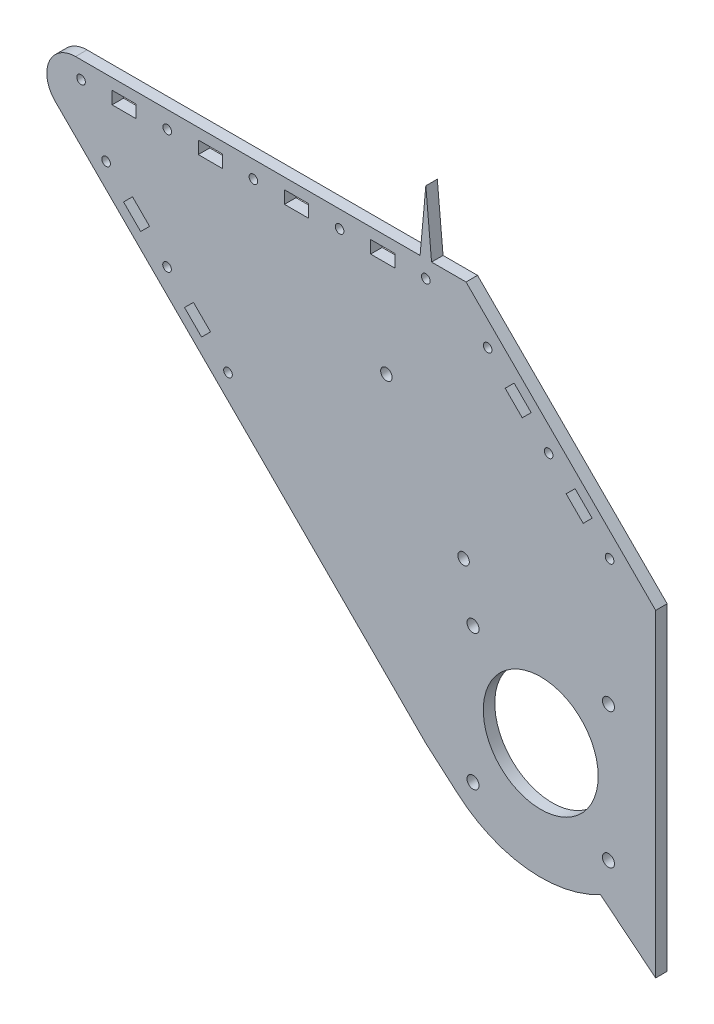
SolidWorks part; units mm, degrees
ref_plane "前视基准面" through (0, 0, 0) normal (0, 0, 1) x (1, 0, 0)
ref_plane "上视基准面" through (0, 0, 0) normal (0, 1, 0) x (1, 0, 0)
ref_plane "右视基准面" through (0, 0, 0) normal (1, 0, 0) x (0, 0, -1)
sketch "草图1" plane through (0, 0, 0) normal (0, 0, 1) x (1, 0, 0)
  line L261 (47.0274, 35.0547) -> (47.0274, 15.0547) construction
  line L315 (7.0274, -5.0025) -> (18.1903, -14.687)
  line L316 (-52.9726, 135.0547) -> (-52.9726, 126.7057) construction
  line L332 (-112.9726, 135.0547) -> (-97.9726, 135.0547) construction
  line L334 (-42.1726, 137.2547) -> (-33.7726, 137.2547)
  line L335 (-42.1726, 137.2547) -> (-42.1726, 132.8547)
  line L336 (-42.1726, 132.8547) -> (-33.7726, 132.8547)
  line L337 (-33.7726, 137.2547) -> (-33.7726, 132.8547)
  line L338 (-42.1726, 137.2547) -> (-33.7726, 132.8547) construction
  line L339 (-42.1726, 132.8547) -> (-33.7726, 137.2547) construction
  line L389 (-114.8877, 141.0547) -> (21.0274, 141.0547)
  line L390 (-22.9726, 135.0547) -> (-22.9726, 144.5851) construction
  line L395 (-37.9726, 135.0547) -> (-7.9726, 135.0547) construction
  line L418 (87.0274, 75.0547) -> (21.0274, 141.0547)
  line L419 (-3.7726, 132.8547) -> (-12.1726, 137.2547) construction
  line L420 (-3.7726, 137.2547) -> (-12.1726, 132.8547) construction
  line L421 (7.0274, 135.0547) -> (-7.9726, 135.0547) construction
  line L422 (-12.1726, 137.2547) -> (-12.1726, 132.8547)
  line L423 (-3.7726, 132.8547) -> (-12.1726, 132.8547)
  line L424 (-3.7726, 137.2547) -> (-3.7726, 132.8547)
  line L443 (-3.7726, 137.2547) -> (-12.1726, 137.2547)
  line L444 (-102.1726, 137.2547) -> (-93.7726, 132.8547) construction
  line L445 (-102.1726, 132.8547) -> (-93.7726, 137.2547) construction
  line L446 (7.0274, -5.0025) -> (-139.0298, 141.0547) construction
  line L447 (-67.9726, 135.0547) -> (-97.9726, 135.0547) construction
  line L448 (47.0274, 15.0547) -> (7.0431, -54.2363) construction
  line L449 (-63.7726, 132.8547) -> (-72.1726, 137.2547) construction
  line L483 (-63.7726, 137.2547) -> (-72.1726, 132.8547) construction
  line L515 (47.0274, 35.0547) -> (47.0274, 135.0547) construction
  line L516 (47.0274, 135.0547) -> (-52.9726, 135.0547) construction
  line L517 (-102.1726, 137.2547) -> (-93.7726, 137.2547)
  line L518 (-102.1726, 137.2547) -> (-102.1726, 132.8547)
  line L519 (-102.1726, 132.8547) -> (-93.7726, 132.8547)
  line L520 (-93.7726, 137.2547) -> (-93.7726, 132.8547)
  line L521 (-72.1726, 137.2547) -> (-72.1726, 132.8547)
  line L522 (-63.7726, 132.8547) -> (-72.1726, 132.8547)
  line L523 (-63.7726, 137.2547) -> (-63.7726, 132.8547)
  line L524 (-63.7726, 137.2547) -> (-72.1726, 137.2547)
  line L525 (7.0274, -5.0025) -> (-7.4159, -49.5482) construction
  line L551 (7.0274, -5.0025) -> (87.0274, -5.0025) construction
  line L552 (7.0274, -5.0025) -> (7.0274, 75.0547) construction
  line L553 (7.0274, 75.0547) -> (87.0274, 75.0547) construction
  line L554 (87.0274, -5.0025) -> (87.0274, 75.0547)
  line L555 (87.0274, -5.0025) -> (17.0006, -65.7205) construction
  line L556 (21.4033, 132.1936) -> (81.3921, 72.2048) construction
  line L557 (54.0274, 108.0547) -> (35.0674, 89.0947) construction
  line L558 (43.7037, 113.0045) -> (34.6527, 115.8329) construction
  line L559 (55.8659, 94.6197) -> (61.8056, 88.68)
  line L576 (55.8659, 94.6197) -> (58.9772, 97.731)
  line L577 (58.9772, 97.731) -> (64.9169, 91.7913)
  line L578 (61.8056, 88.68) -> (64.9169, 91.7913)
  line L579 (55.8659, 94.6197) -> (64.9169, 91.7913) construction
  line L580 (58.9772, 97.731) -> (61.8056, 88.68) construction
  line L581 (40.5924, 109.8932) -> (37.764, 118.9442) construction
  line L582 (34.6527, 115.8329) -> (37.764, 118.9442)
  line L583 (43.7037, 113.0045) -> (37.764, 118.9442)
  line L584 (40.5924, 109.8932) -> (43.7037, 113.0045)
  line L585 (40.5924, 109.8932) -> (34.6527, 115.8329)
  line L586 (60.3914, 93.2055) -> (58.8358, 91.6499) construction
  line L587 (39.1782, 114.4187) -> (37.6226, 112.8631) construction
  line L594 (75.8488, -14.6951) -> (87.0274, -5.0025)
  line L599 (-90.2039, 92.2289) -> (-121.9587, 123.9837)
  line L600 (-73.8521, 87.4736) -> (-76.9634, 84.3624)
  line L605 (-25.9726, 27.9975) -> (-21.7299, 32.2402) construction
  line L607 (-83.0445, 93.5547) -> (-87.2872, 89.3121) construction
  line L608 (-90.2039, 92.2289) -> (7.0274, -5.0025)
  line L621 (-83.0445, 93.5547) -> (-61.8313, 72.3415) construction
  line L622 (-73.8521, 87.4736) -> (-67.9124, 81.5339)
  line L623 (47.0274, 15.0547) -> (89.2922, -52.8694) construction
  line L624 (89.2922, -52.8694) -> (7.0274, -54.2273) construction
  line L625 (-76.9634, 84.3624) -> (-71.0237, 78.4227)
  line L630 (-67.9124, 81.5339) -> (-71.0237, 78.4227)
  line L631 (-73.8521, 87.4736) -> (-71.0237, 78.4227) construction
  line L632 (-82.9726, 135.0547) -> (-82.9726, 64.2144) construction
  line L633 (-76.9634, 84.3624) -> (-67.9124, 81.5339) construction
  line L634 (-89.1256, 102.7471) -> (-92.2369, 99.6359)
  line L635 (-92.2369, 99.6359) -> (-98.1766, 105.5756)
  line L636 (-95.0653, 108.6868) -> (-98.1766, 105.5756)
  line L637 (-89.1256, 102.7471) -> (-95.0653, 108.6868)
  line L638 (-22.9726, 135.0547) -> (-22.9726, 124.9547) construction
  line L639 (-22.9726, 124.9547) -> (47.0274, 15.0547) construction
  circle A39 centre (-52.9726, 135.0547) radius 1.5
  circle A42 centre (47.0274, 15.0547) radius 20
  circle A49 centre (-22.9726, 135.0547) radius 1.5
  circle A69 centre (7.0274, 135.0547) radius 1.5
  circle A92 centre (-112.9726, 135.0547) radius 1.5
  circle A93 centre (-82.9726, 135.0547) radius 1.5
  circle A94 centre (7.0431, -54.2363) radius 5.2 construction
  circle A96 centre (7.0431, -54.2363) radius 15.2 construction
  circle A98 centre (49.7848, 103.8121) radius 1.5
  circle A99 centre (70.998, 82.5989) radius 1.5
  circle A100 centre (28.5716, 125.0253) radius 1.5
  circle A107 centre (70.5974, 38.6247) radius 2.1
  circle A108 centre (70.5974, -8.5153) radius 2.1
  circle A109 centre (23.4574, -8.5153) radius 2.1
  circle A110 centre (23.4574, 38.6247) radius 2.1
  arc A111 (75.8488, -14.6951) -> (18.1903, -14.687) centre (47.0242, 18.5486) cw
  arc A115 (-114.8877, 141.0547) -> (-121.9587, 123.9837) centre (-114.8877, 131.0547) ccw
  circle A116 centre (-83.0445, 93.5547) radius 1.5
  circle A117 centre (-61.8313, 72.3415) radius 1.5
  circle A118 centre (-104.2577, 114.7679) radius 1.5
  circle A121 centre (20.1663, 57.2267) radius 2
  circle A122 centre (-6.6949, 99.3988) radius 2
  point P5 (210.9534, 218.4629)
  point P6 (288.6284, 218.4629)
  point P54 (-105.4726, 135.0547)
  point P60 (60.3914, 93.2055)
  point P88 (-72.4379, 82.9481)
  point P115 (47.016, -39.6951)
  dimension "D1" = 40
  dimension "D3" = 40
  dimension "D5" = 23.57
  dimension "D4" = 4.2
  dimension "D6" = 23.57
  dimension "D2" = 40
  dimension "D7" = 6
  dimension "D12" = 3
  dimension "D19" = 10.4
  dimension "D20" = 10
  dimension "D22" = 3
  dimension "D8" = 30
  dimension "D28" = 44
  dimension "D26" = 10
  dimension "D17" = 10.1
  dimension "D29" = 50
  dimension "D30" = 50
  dimension "D9" = 15
  dimension "D10" = 15
  dimension "D11" = 8.4
  dimension "D13" = 4.4
  dimension "D14" = 6
  dimension "D15" = 45
  dimension "D16" = 41.5
  dimension "D18" = 80
  dimension "D21" = 6
  dimension "D23" = 15
  dimension "D24" = 8.4
  dimension "D25" = 4.4
  dimension "D27" = 4
extrude "凸台-拉伸1" add sketch "草图1" along normal blind 4
sketch "草图2" plane through (0, 0, 4) normal (0, 0, 1) x (1, 0, 0)
  line L0 (87.0274, -5.0025) -> (87.0274, -35.7541)
  line L1 (87.0274, -35.7541) -> (67.8118, -20.2312)
  line L2 (67.8118, -20.2312) -> (87.0274, -5.0025)
  arc A0 (18.1903, -14.687) -> (75.8488, -14.6951) centre (47.0242, 18.5486) ccw construction
extrude "凸台-拉伸2" add sketch "草图2" against normal blind 4
sketch "草图3" plane through (0, 0, 4) normal (0, 0, 1) x (1, 0, 0)
  line L6 (21.0274, 141.0547) -> (-114.8877, 141.0547) construction
  line L10 (7.0274, 135.0547) -> (7.0274, 141.0547) construction
  line L11 (7.0274, 141.0547) -> (7.0274, 163.0547) construction
  line L12 (7.0274, 141.0547) -> (5.0274, 141.0547)
  line L13 (5.0274, 141.0547) -> (7.0274, 163.0547)
  line L14 (7.0274, 141.0547) -> (9.0274, 141.0547)
  line L15 (9.0274, 141.0547) -> (7.0274, 163.0547)
extrude "凸台-拉伸4" add sketch "草图3" against normal blind 4
